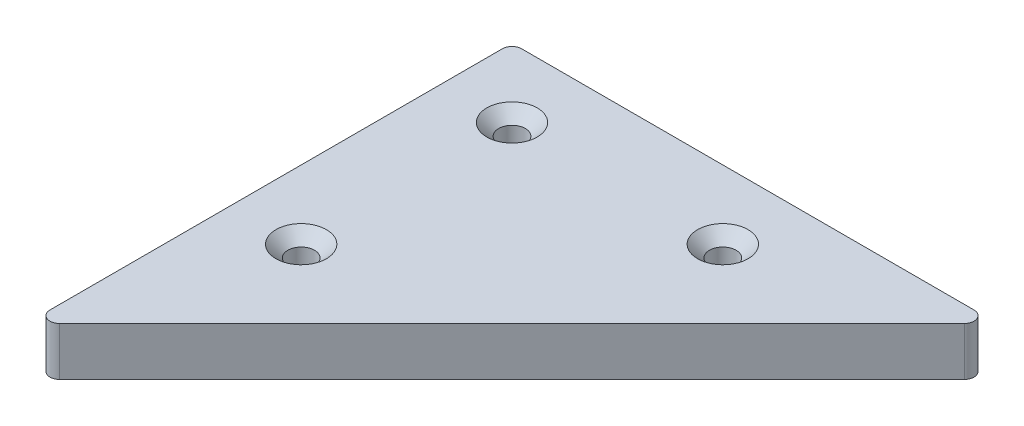
SolidWorks part; units mm, degrees
material "2219-O"
ref_plane "Front Plane" through (0, 0, 0) normal (0, 0, 1) x (1, 0, 0)
ref_plane "Top Plane" through (0, 0, 0) normal (0, 1, 0) x (1, 0, 0)
ref_plane "Right Plane" through (0, 0, 0) normal (1, 0, 0) x (0, 0, -1)
sketch "Sketch1" plane through (0, 0, 0) normal (0, 1, 0) x (1, 0, 0)
  line L0 (0, 0) -> (0, -100)
  line L1 (0, -100) -> (100, 0)
  line L2 (100, 0) -> (0, 0)
  dimension "D1" = 100
extrude "Boss-Extrude1" add sketch "Sketch1" along normal blind 10
sketch "Sketch2" plane through (0, 10, 0) normal (0, 1, 0) x (1, 0, 0)
  line L0 (0, 0) -> (35355.3391, -35355.3391) construction
  line L1 (0, -100) -> (100, 0) construction
  line L2 (14.1421, -57.5736) -> (14.1421, -14.1421) construction
  line L3 (57.5736, -14.1421) -> (14.1421, -14.1421) construction
  dimension "D1" = 20
  dimension "D2" = 20
hole_wizard "CSK for M5 Flat Head Machine Screw1" positions "3DSketch1" profile "Sketch4" countersink size "M5" standard "ANSI Metric" end condition through all
sketch3d "3DSketch1"
  point P0 (14.1421, 10, 14.1421)
  point P3 (14.1421, 10, 57.5736)
  point P6 (57.5736, 10, 14.1421)
sketch "Sketch4" plane through (14.1421, 10, 14.1421) normal (1, 0, 0) x (0, 0, 1)
  line L0 (0, 0) -> (0, 10)
  line L1 (0, 10) -> (2.75, 10)
  line L2 (2.75, 10) -> (2.75, 2.45)
  line L3 (2.75, 2.45) -> (5.2, 0)
  line L5 (5.2, 0) -> (0, 0)
  line L6 (-2.75, 2.45) -> (-5.2, 0) construction
  line L11 (0, -6.35) -> (0, 107.95) construction
  dimension "Thru Hole Dia." = 5.5
  dimension "Thru Hole Depth" = 10
  dimension "Near C'Sink Dia." = 10.4
  dimension "Near C'Sink Angle" = 90
fillet "Fillet2" radius 2 3 edges at (0, 5, 0) (100, 5, 0) (0, 5, 100)
